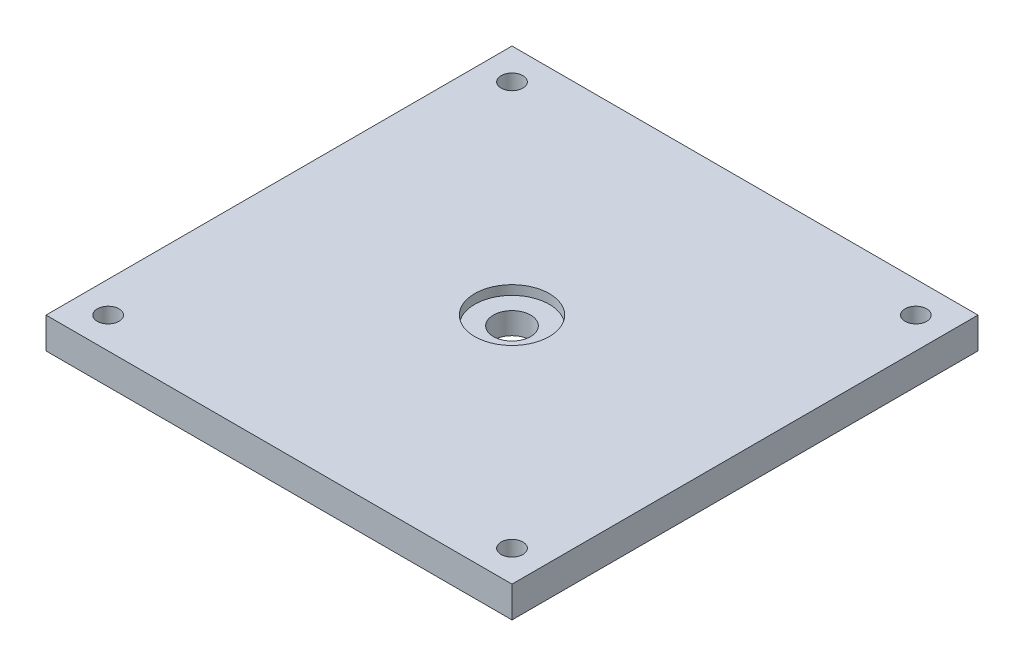
SolidWorks part; units mm, degrees
material "6061 Alloy"
ref_plane "Plano frontal" through (0, 0, 0) normal (0, 0, 1) x (1, 0, 0)
ref_plane "Plano superior" through (0, 0, 0) normal (0, 1, 0) x (1, 0, 0)
ref_plane "Plano direito" through (0, 0, 0) normal (1, 0, 0) x (0, 0, -1)
sketch "Sketch1" plane through (0, 0, 0) normal (0, 1, 0) x (1, 0, 0)
  line L1 (-75, 75) -> (75, 75)
  line L2 (-75, 75) -> (-75, -75)
  line L3 (-75, -75) -> (75, -75)
  line L4 (75, 75) -> (75, -75)
  line L5 (-75, 75) -> (75, -75) construction
  line L6 (-75, -75) -> (75, 75) construction
  point P0 (0, 0)
  dimension "D1" = 150
extrude "Boss-Extrude1" add sketch "Sketch1" along normal blind 10
sketch "Sketch2" plane through (0, 10, 0) normal (0, 1, 0) x (1, 0, 0)
  circle A0 centre (0, 0) radius 12
  dimension "D1" = 24
extrude "Cut-Extrude1" cut sketch "Sketch2" against normal blind 3
sketch "Sketch3" plane through (0, 7, 0) normal (0, 1, 0) x (1, 0, 0)
  circle A0 centre (0, 0) radius 6
  dimension "D1" = 12
extrude "Cut-Extrude2" cut sketch "Sketch3" against normal up to surface (7 mm away) up to face at (0, 0, 0)
hole_wizard "Hole1" positions "3DSketch1" profile "Sketch4" legacy
sketch3d "3DSketch1"
  line L0 (-75, 0, 75) -> (75, 0, 75) construction
  line L1 (-75, 0, -75) -> (-75, 0, 75) construction
  line L2 (75, 0, 75) -> (75, 0, -75) construction
  line L3 (75, 0, -75) -> (-75, 0, -75) construction
  point P0 (65, 0, 65)
  point P2 (65, 0, -65)
  point P4 (-65, 0, -65)
  point P6 (-65, 0, 65)
  dimension "D1" = 10
  dimension "D2" = 10
  dimension "D5" = 10
  dimension "D6" = 10
sketch "Sketch4" plane through (65, 0, 65) normal (1, 0, 0) x (0, 0, -1)
  line L0 (0, 0) -> (0, 10)
  line L1 (0, 10) -> (3.5, 10)
  line L2 (3.5, 10) -> (3.5, 0)
  line L5 (3.5, 0) -> (0, 0)
  line L11 (0, -6.35) -> (0, 107.95) construction
  dimension "Thru Tap Drill Dia." = 7
  dimension "Thru Tap Drill Depth" = 10
hole_wizard "M2.5 Tapped Hole1" positions "3DSketch2" profile "Sketch6" tap size "M2.5" standard "DIN"
sketch3d "3DSketch2"
  circle A2 centre (0, 0, 0) radius 9.525 construction
  point P0 (-9.525, 0, 0)
  point P2 (9.525, 0, 0)
  point P13 (0, 9.525, 0)
  dimension "D1" = 19.05
sketch "Sketch6" plane through (-9.525, 0, 0) normal (1, 0, 0) x (0, 0, -1)
  line L0 (0, 0) -> (0, 5.9659)
  line L1 (0, 5.9659) -> (1.025, 5.35)
  line L2 (1.025, 5.35) -> (1.025, 0)
  line L5 (1.025, 0) -> (0, 0)
  line L10 (0, 5.9659) -> (-1.025, 5.35) construction
  line L11 (0, -6.35) -> (0, 107.95) construction
  dimension "Tap Drill Dia." = 2.05
  dimension "Tap Drill Depth" = 5.35
  dimension "Drill Angle" = 118
cosmetic thread "Hole Thread1" parameters "D1"=4, "D2"=2.5
cosmetic thread "Hole Thread2" parameters "D1"=4, "D2"=2.5
